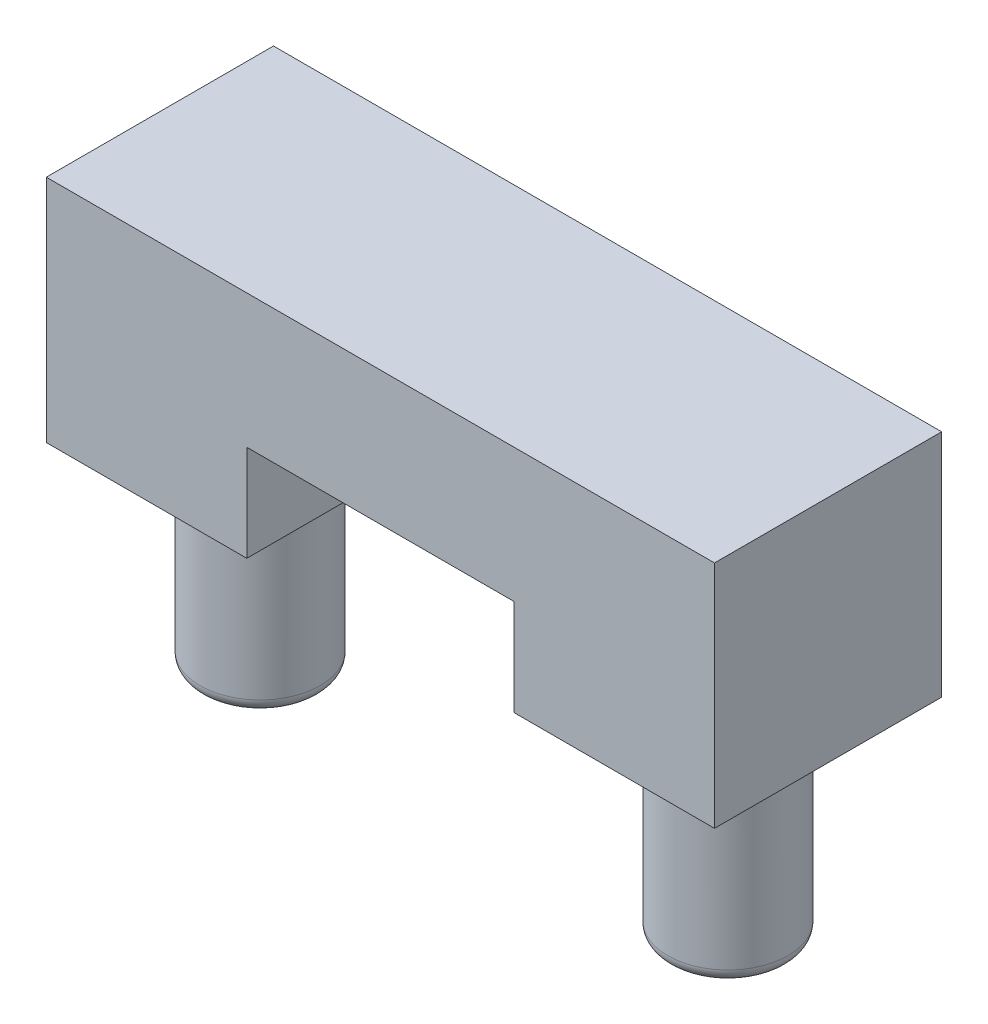
SolidWorks part; units mm, degrees
ref_plane "Front Plane" through (0, 0, 0) normal (0, 0, 1) x (1, 0, 0)
ref_plane "Top Plane" through (0, 0, 0) normal (0, 1, 0) x (1, 0, 0)
ref_plane "Right Plane" through (0, 0, 0) normal (1, 0, 0) x (0, 0, -1)
sketch "Sketch1" plane through (0, 0, 0) normal (0, 1, 0) x (1, 0, 0)
  line L1 (-25, 8.5) -> (25, 8.5)
  line L2 (-25, 8.5) -> (-25, -8.5)
  line L3 (-25, -8.5) -> (25, -8.5)
  line L4 (25, 8.5) -> (25, -8.5)
  line L5 (-25, 8.5) -> (25, -8.5) construction
  line L6 (-25, -8.5) -> (25, 8.5) construction
  point P0 (0, 0)
  dimension "D1" = 50
  dimension "D2" = 17
extrude "Boss-Extrude1" add sketch "Sketch1" along normal blind 10
sketch "Sketch2" plane through (0, 0, 0) normal (0, -1, 0) x (1, 0, 0)
  line L0 (-25, 8.5) -> (25, 8.5) construction
  line L1 (-25, -8.5) -> (-10, -8.5)
  line L2 (-25, -8.5) -> (-25, 8.5)
  line L3 (-25, 8.5) -> (-10, 8.5)
  line L4 (-10, -8.5) -> (-10, 8.5)
  line L5 (25, -8.5) -> (-25, -8.5) construction
  line L6 (25, 8.5) -> (10, 8.5)
  line L7 (25, 8.5) -> (25, -8.5)
  line L8 (25, -8.5) -> (10, -8.5)
  line L9 (10, 8.5) -> (10, -8.5)
  dimension "D1" = 15
  dimension "D2" = 15
extrude "Boss-Extrude2" add sketch "Sketch2" along normal blind 7.2
sketch "Sketch3" plane through (0, -7.2, 0) normal (0, -1, 0) x (1, 0, 0)
  line L0 (-25, 0) -> (25, 0) construction
  line L1 (-25, 8.5) -> (-25, -8.5) construction
  line L2 (25, -8.5) -> (25, 8.5) construction
  line L3 (10, 8.5) -> (10, -8.5) construction
  line L4 (-10, -8.5) -> (-10, 8.5) construction
  circle A0 centre (-17.5, 0) radius 4.5
  circle A1 centre (17.5, 0) radius 4.5
  dimension "D1" = 9
  dimension "D2" = 9
  dimension "D3" = 7.5
  dimension "D4" = 7.5
extrude "Boss-Extrude3" add sketch "Sketch3" along normal blind 15
fillet "Fillet1" radius 1 2 edges at (17.5, -22.2, -4.5) (-17.5, -22.2, -4.5)
